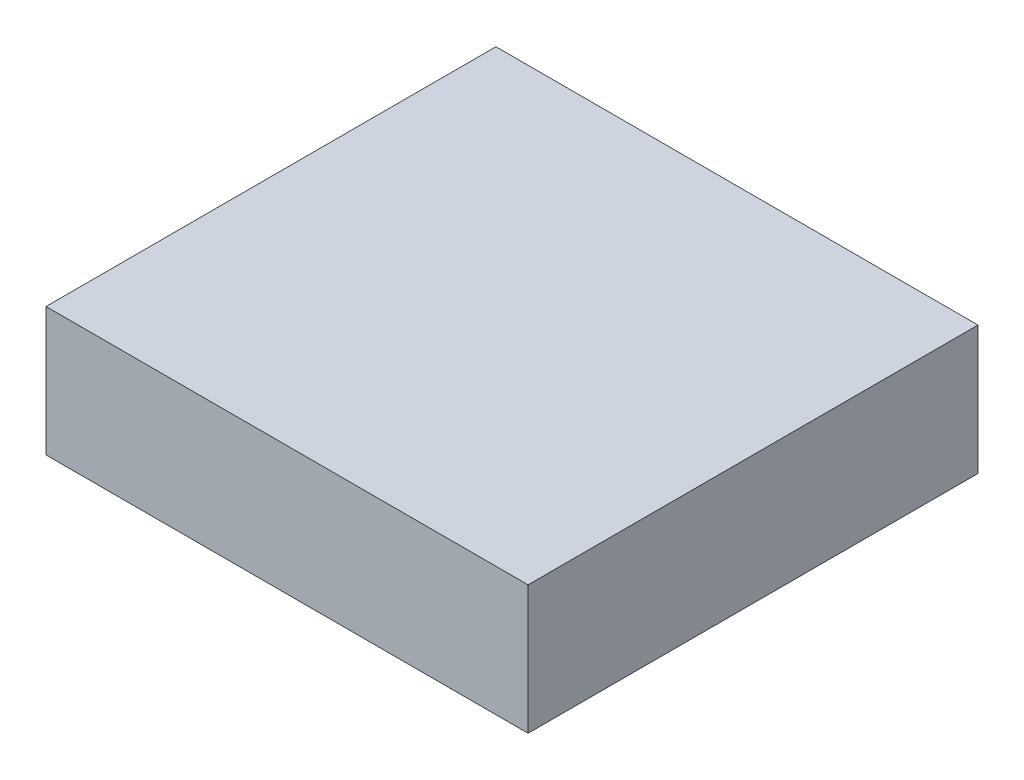
SolidWorks part; units mm, degrees
ref_plane "Front" through (0, 0, 0) normal (0, 0, 1) x (1, 0, 0)
ref_plane "Top" through (0, 0, 0) normal (0, 1, 0) x (1, 0, 0)
ref_plane "Right" through (0, 0, 0) normal (1, 0, 0) x (0, 0, -1)
sketch "Sketch1" plane through (0, 0, 0) normal (0, 1, 0) x (1, 0, 0)
  line L1 (-21.7949, 16.4103) -> (23.2051, 16.4103)
  line L2 (-21.7949, 16.4103) -> (-21.7949, -25.5897)
  line L3 (-21.7949, -25.5897) -> (23.2051, -25.5897)
  line L4 (23.2051, 16.4103) -> (23.2051, -25.5897)
  dimension "D1" = 45
  dimension "D2" = 42
extrude "Boss-Extrude1" add sketch "Sketch1" along normal blind 12
